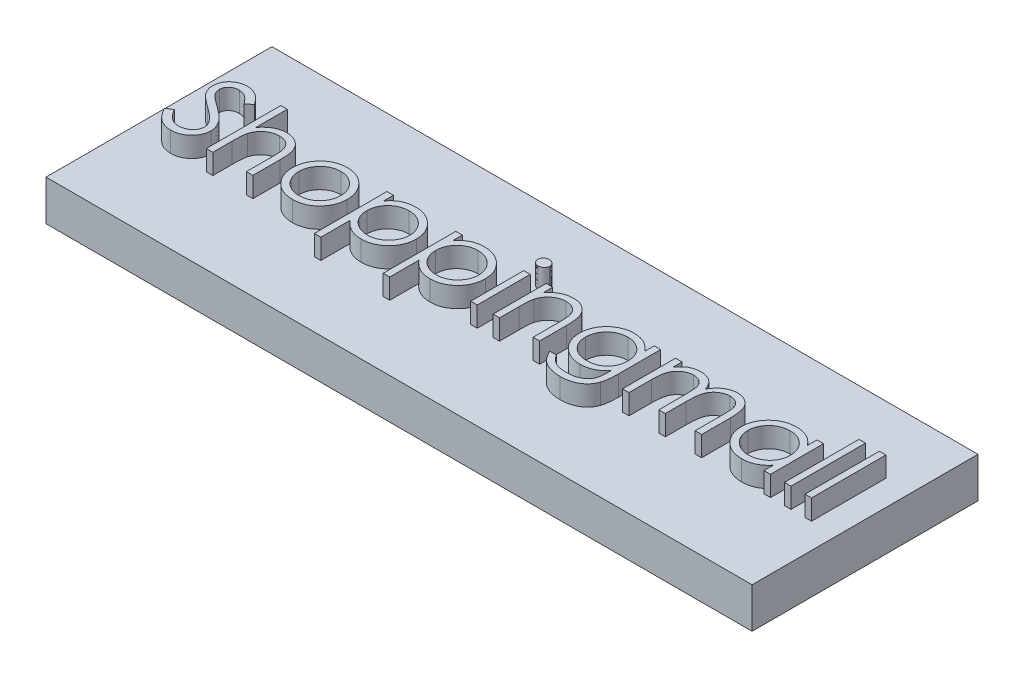
SolidWorks part; units mm, degrees
ref_plane "Front Plane" through (0, 0, 0) normal (0, 0, 1) x (1, 0, 0)
ref_plane "Top Plane" through (0, 0, 0) normal (0, 1, 0) x (1, 0, 0)
ref_plane "Right Plane" through (0, 0, 0) normal (1, 0, 0) x (0, 0, -1)
sketch "Sketch1" plane through (0, 0, 0) normal (0, 1, 0) x (1, 0, 0)
  line L1 (-87.5, 28) -> (87.5, 28)
  line L2 (-87.5, 28) -> (-87.5, -28)
  line L3 (-87.5, -28) -> (87.5, -28)
  line L4 (87.5, 28) -> (87.5, -28)
  line L5 (-87.5, 28) -> (87.5, -28) construction
  line L6 (-87.5, -28) -> (87.5, 28) construction
  point P0 (0, 0)
  dimension "D1" = 175
  dimension "D2" = 56
extrude "Boss-Extrude1" add sketch "Sketch1" along normal blind 10
sketch "Sketch2" plane through (0, 10, 0) normal (0, 1, 0) x (1, 0, 0)
  line L0 (-87.5, -7) -> (87.5, -7) construction
  line L1 (-87.5, 28) -> (-87.5, -28) construction
  line L2 (87.5, -28) -> (87.5, 28) construction
  line L3 (87.5, 28) -> (-87.5, 28) construction
  text T0 "Shoppingmall" font "Century Gothic" height 18
  dimension "D1" = 35
extrude "Boss-Extrude2" add sketch "Sketch2" along normal blind 5 separate body
